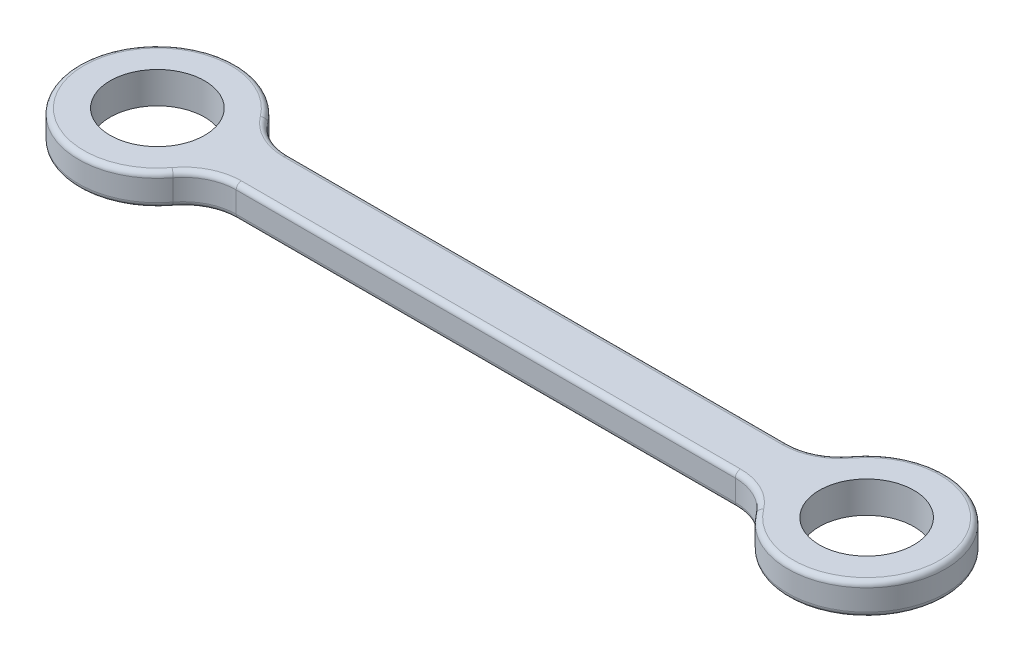
SolidWorks part; units mm, degrees
ref_plane "Front Plane" through (0, 0, 0) normal (0, 0, 1) x (1, 0, 0)
ref_plane "Top Plane" through (0, 0, 0) normal (0, 1, 0) x (1, 0, 0)
ref_plane "Right Plane" through (0, 0, 0) normal (1, 0, 0) x (0, 0, -1)
sketch "Sketch1" plane through (0, 0, 0) normal (0, 1, 0) x (1, 0, 0)
  line L1 (-28.046, 5) -> (66.954, 5)
  line L3 (-28.046, -5) -> (66.954, -5)
  circle A0 centre (-48.046, 0) radius 9
  circle A1 centre (86.954, 0) radius 9
  arc A2 (-36.046, 9) -> (-36.046, -9) centre (-48.046, 0) ccw
  arc A3 (74.954, -9) -> (74.954, 9) centre (86.954, 0) ccw
  arc A4 (74.954, 9) -> (66.954, 5) centre (66.954, 15) cw
  arc A5 (74.954, -9) -> (66.954, -5) centre (66.954, -15) ccw
  arc A6 (-28.046, -5) -> (-36.046, -9) centre (-28.046, -15) ccw
  arc A7 (-28.046, 5) -> (-36.046, 9) centre (-28.046, 15) cw
  point P6 (-48.046, 5)
  point P8 (31.954, 5)
  point P9 (-48.046, -5)
  point P10 (49.3563, -5)
  dimension "D1" = 18
  dimension "D2" = 18
  dimension "D3" = 30
  dimension "D4" = 30
  dimension "D5" = 10
  dimension "D6" = 135
  dimension "D7" = 10
extrude "Boss-Extrude1" add sketch "Sketch1" along normal blind 6
fillet "Fillet1" radius 1 16 edges at (-63.046, 0, 0) (-32.5181, 0, -6.0557) (19.454, 0, -5) (71.4262, 0, -6.0557) (101.954, 0, 0) (71.4262, 0, 6.0557) (19.454, 0, 5) (-32.5181, 6, 6.0557) (-63.046, 6, 0) (-32.5181, 6, -6.0557) (19.454, 6, -5) (71.4262, 6, -6.0557) (101.954, 6, 0) (71.4262, 6, 6.0557) (-32.5181, 0, 6.0557) (19.454, 6, 5)
